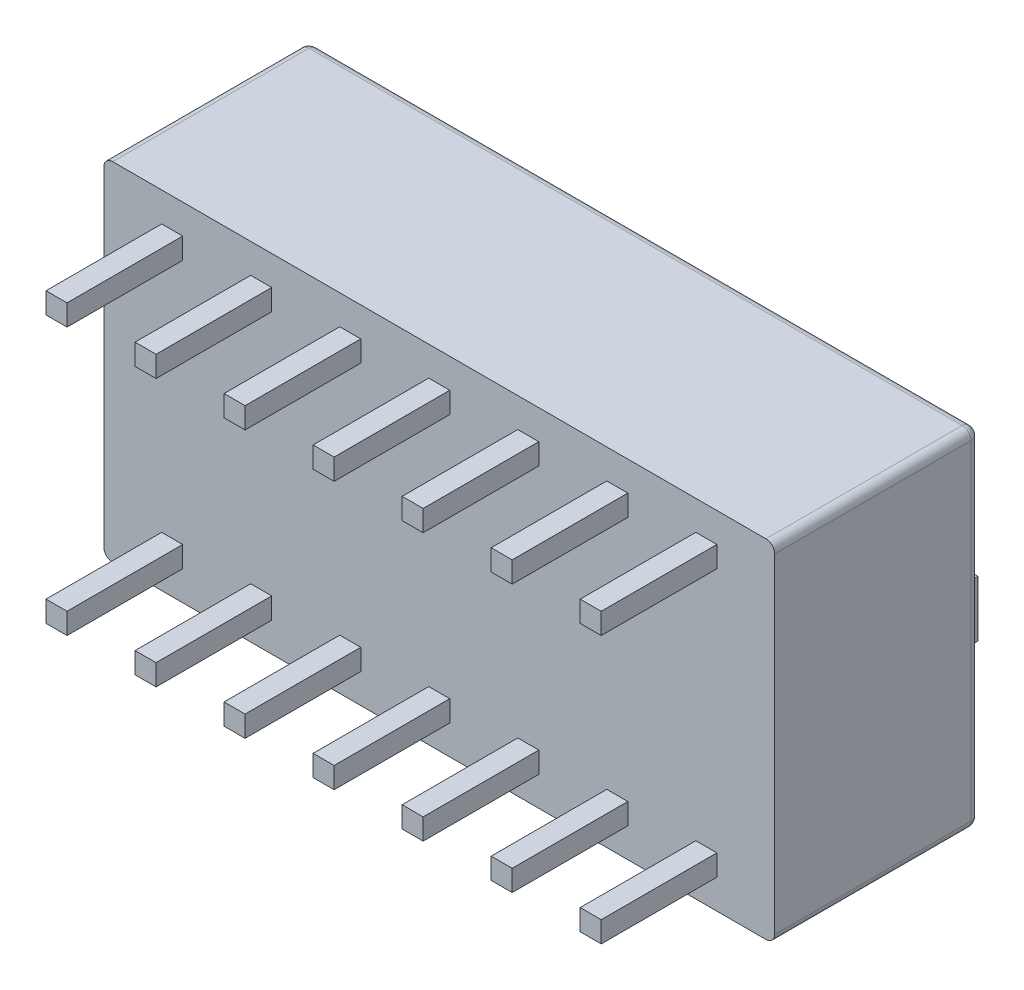
SolidWorks part; units mm, degrees
ref_plane "Ön Düzlem" through (0, 0, 0) normal (0, 0, 1) x (1, 0, 0)
ref_plane "Üst Düzlem" through (0, 0, 0) normal (0, 1, 0) x (1, 0, 0)
ref_plane "Sağ Düzlem" through (0, 0, 0) normal (1, 0, 0) x (0, 0, -1)
sketch "Çizim1" plane through (0, 0, 0) normal (0, 0, 1) x (1, 0, 0)
  line L1 (-9.57, 4.95) -> (9.57, 4.95)
  line L2 (-9.57, 4.95) -> (-9.57, -4.95)
  line L3 (-9.57, -4.95) -> (9.57, -4.95)
  line L4 (9.57, 4.95) -> (9.57, -4.95)
  line L5 (-9.57, 4.95) -> (9.57, -4.95) construction
  line L6 (-9.57, -4.95) -> (9.57, 4.95) construction
  point P0 (0, 0)
extrude "Yükseklik-Ekstrüzyon1" add sketch "Çizim1" along normal blind 5.85
sketch "Çizim2" plane through (0, 0, 0) normal (0, 0, -1) x (-1, 0, 0)
  line L8 (-8.32, 1.6) -> (-6.92, 1.6)
  line L9 (-8.32, 1.6) -> (-8.32, -1.6)
  line L10 (-8.32, -1.6) -> (-6.92, -1.6)
  line L11 (-6.92, 1.6) -> (-6.92, -1.6)
  line L12 (-8.32, 1.6) -> (-6.92, -1.6) construction
  line L13 (-8.32, -1.6) -> (-6.92, 1.6) construction
  line L14 (-5.78, 1.6) -> (-4.38, 1.6)
  line L15 (-5.78, 1.6) -> (-5.78, -1.6)
  line L16 (-5.78, -1.6) -> (-4.38, -1.6)
  line L17 (-4.38, 1.6) -> (-4.38, -1.6)
  line L18 (-5.78, 1.6) -> (-4.38, -1.6) construction
  line L19 (-5.78, -1.6) -> (-4.38, 1.6) construction
  line L20 (-3.24, 1.6) -> (-1.84, 1.6)
  line L21 (-3.24, 1.6) -> (-3.24, -1.6)
  line L22 (-3.24, -1.6) -> (-1.84, -1.6)
  line L23 (-1.84, 1.6) -> (-1.84, -1.6)
  line L24 (-3.24, 1.6) -> (-1.84, -1.6) construction
  line L25 (-3.24, -1.6) -> (-1.84, 1.6) construction
  line L26 (-0.7, 1.6) -> (0.7, 1.6)
  line L27 (-0.7, 1.6) -> (-0.7, -1.6)
  line L28 (-0.7, -1.6) -> (0.7, -1.6)
  line L29 (0.7, 1.6) -> (0.7, -1.6)
  line L30 (-0.7, 1.6) -> (0.7, -1.6) construction
  line L31 (-0.7, -1.6) -> (0.7, 1.6) construction
  line L32 (1.84, 1.6) -> (3.24, 1.6)
  line L33 (1.84, 1.6) -> (1.84, -1.6)
  line L34 (1.84, -1.6) -> (3.24, -1.6)
  line L35 (3.24, 1.6) -> (3.24, -1.6)
  line L36 (1.84, 1.6) -> (3.24, -1.6) construction
  line L37 (1.84, -1.6) -> (3.24, 1.6) construction
  line L38 (4.38, 1.6) -> (5.78, 1.6)
  line L39 (4.38, 1.6) -> (4.38, -1.6)
  line L40 (4.38, -1.6) -> (5.78, -1.6)
  line L41 (5.78, 1.6) -> (5.78, -1.6)
  line L42 (4.38, 1.6) -> (5.78, -1.6) construction
  line L43 (4.38, -1.6) -> (5.78, 1.6) construction
  line L44 (6.92, 1.6) -> (8.32, 1.6)
  line L45 (6.92, 1.6) -> (6.92, -1.6)
  line L46 (6.92, -1.6) -> (8.32, -1.6)
  line L47 (8.32, 1.6) -> (8.32, -1.6)
  line L48 (6.92, 1.6) -> (8.32, -1.6) construction
  line L49 (6.92, -1.6) -> (8.32, 1.6) construction
extrude "Kes-Ekstrüzyon1" cut sketch "Çizim2" against normal blind 1
sketch "Çizim3" plane through (0, 0, 1) normal (0, 0, -1) x (-1, 0, 0)
  line L0 (-6.92, -1.6) -> (-6.92, 1.6) construction
  line L1 (-8.32, -1.6) -> (-6.92, -1.6)
  line L2 (-8.32, -1.6) -> (-8.32, 0)
  line L3 (-8.32, 0) -> (-6.92, 0)
  line L4 (-6.92, -1.6) -> (-6.92, 0)
  line L5 (-5.78, 1.6) -> (-5.78, -1.6) construction
  line L6 (-5.78, 0) -> (-4.38, 0)
  line L7 (-5.78, 0) -> (-5.78, -1.6)
  line L8 (-5.78, -1.6) -> (-4.38, -1.6)
  line L9 (-4.38, 0) -> (-4.38, -1.6)
  line L10 (-3.24, 1.6) -> (-3.24, -1.6) construction
  line L11 (-3.24, 0) -> (-1.84, 0)
  line L12 (-3.24, 0) -> (-3.24, -1.6)
  line L13 (-3.24, -1.6) -> (-1.84, -1.6)
  line L14 (-1.84, 0) -> (-1.84, -1.6)
  line L15 (-0.7, 1.6) -> (-0.7, -1.6) construction
  line L16 (-0.7, 0) -> (0.7, 0)
  line L17 (-0.7, 0) -> (-0.7, -1.6)
  line L18 (-0.7, -1.6) -> (0.7, -1.6)
  line L19 (0.7, 0) -> (0.7, -1.6)
  line L20 (1.84, 1.6) -> (1.84, -1.6) construction
  line L21 (1.84, 0) -> (3.24, 0)
  line L22 (1.84, 0) -> (1.84, -1.6)
  line L23 (1.84, -1.6) -> (3.24, -1.6)
  line L24 (3.24, 0) -> (3.24, -1.6)
  line L25 (4.38, 1.6) -> (4.38, -1.6) construction
  line L26 (4.38, 0) -> (5.78, 0)
  line L27 (4.38, 0) -> (4.38, -1.6)
  line L28 (4.38, -1.6) -> (5.78, -1.6)
  line L29 (5.78, 0) -> (5.78, -1.6)
  line L30 (6.92, 1.6) -> (6.92, -1.6) construction
  line L31 (6.92, 0) -> (8.32, 0)
  line L32 (6.92, 0) -> (6.92, -1.6)
  line L33 (6.92, -1.6) -> (8.32, -1.6)
  line L34 (8.32, 0) -> (8.32, -1.6)
extrude "Yükseklik-Ekstrüzyon2" add sketch "Çizim3" along normal blind 2.2 separate body
sketch "Çizim4" plane through (0, 0, 1) normal (0, 0, -1) x (-1, 0, 0)
  line L0 (-6.92, -1.6) -> (-6.92, 1.6) construction
  line L1 (-8.32, 1.6) -> (-6.92, 1.6)
  line L2 (-8.32, 1.6) -> (-8.32, 0)
  line L3 (-8.32, 0) -> (-6.92, 0)
  line L4 (-6.92, 1.6) -> (-6.92, 0)
  line L5 (-4.38, -1.6) -> (-4.38, 1.6) construction
  line L6 (-5.78, 1.6) -> (-4.38, 1.6)
  line L7 (-5.78, 1.6) -> (-5.78, 0)
  line L8 (-5.78, 0) -> (-4.38, 0)
  line L9 (-4.38, 1.6) -> (-4.38, 0)
  line L10 (-1.84, -1.6) -> (-1.84, 1.6) construction
  line L11 (-3.24, 1.6) -> (-1.84, 1.6)
  line L12 (-3.24, 1.6) -> (-3.24, 0)
  line L13 (-3.24, 0) -> (-1.84, 0)
  line L14 (-1.84, 1.6) -> (-1.84, 0)
  line L15 (0.7, -1.6) -> (0.7, 1.6) construction
  line L16 (-0.7, 1.6) -> (0.7, 1.6)
  line L17 (-0.7, 1.6) -> (-0.7, 0)
  line L18 (-0.7, 0) -> (0.7, 0)
  line L19 (0.7, 1.6) -> (0.7, 0)
  line L20 (3.24, -1.6) -> (3.24, 1.6) construction
  line L21 (1.84, 1.6) -> (3.24, 1.6)
  line L22 (1.84, 1.6) -> (1.84, 0)
  line L23 (1.84, 0) -> (3.24, 0)
  line L24 (3.24, 1.6) -> (3.24, 0)
  line L25 (5.78, -1.6) -> (5.78, 1.6) construction
  line L26 (4.38, 1.6) -> (5.78, 1.6)
  line L27 (4.38, 1.6) -> (4.38, 0)
  line L28 (4.38, 0) -> (5.78, 0)
  line L29 (5.78, 1.6) -> (5.78, 0)
  line L31 (6.92, 1.6) -> (8.32, 1.6)
  line L32 (6.92, 1.6) -> (6.92, 0)
  line L33 (6.92, 0) -> (8.32, 0)
  line L34 (8.32, 1.6) -> (8.32, 0)
extrude "Yükseklik-Ekstrüzyon3" add sketch "Çizim4" along normal blind 0.9 separate body
fillet "Radyus1" radius 0.25 8 edges at (9.57, -4.95, 2.925) (9.57, 4.95, 2.925) (9.57, 0, 0) (-9.57, -4.95, 2.925) (0, -4.95, 0) (0, 4.95, 0) (-9.57, 4.95, 2.925) (-9.57, 0, 0)
sketch "Çizim5" plane through (0, 0, 5.85) normal (0, 0, 1) x (1, 0, 0)
  line L15 (-7.92, 4.11) -> (-7.32, 4.11)
  line L16 (-7.92, 4.11) -> (-7.92, 3.51)
  line L17 (-7.92, 3.51) -> (-7.32, 3.51)
  line L18 (-7.32, 4.11) -> (-7.32, 3.51)
  line L19 (-7.92, 4.11) -> (-7.32, 3.51) construction
  line L20 (-7.92, 3.51) -> (-7.32, 4.11) construction
  line L21 (-5.38, 4.11) -> (-4.78, 4.11)
  line L22 (-5.38, 4.11) -> (-5.38, 3.51)
  line L23 (-5.38, 3.51) -> (-4.78, 3.51)
  line L24 (-4.78, 4.11) -> (-4.78, 3.51)
  line L25 (-5.38, 4.11) -> (-4.78, 3.51) construction
  line L26 (-5.38, 3.51) -> (-4.78, 4.11) construction
  line L27 (-2.84, 4.11) -> (-2.24, 4.11)
  line L28 (-2.84, 4.11) -> (-2.84, 3.51)
  line L29 (-2.84, 3.51) -> (-2.24, 3.51)
  line L30 (-2.24, 4.11) -> (-2.24, 3.51)
  line L31 (-2.84, 4.11) -> (-2.24, 3.51) construction
  line L32 (-2.84, 3.51) -> (-2.24, 4.11) construction
  line L33 (-0.3, 4.11) -> (0.3, 4.11)
  line L34 (-0.3, 4.11) -> (-0.3, 3.51)
  line L35 (-0.3, 3.51) -> (0.3, 3.51)
  line L36 (0.3, 4.11) -> (0.3, 3.51)
  line L37 (-0.3, 4.11) -> (0.3, 3.51) construction
  line L38 (-0.3, 3.51) -> (0.3, 4.11) construction
  line L39 (2.24, 4.11) -> (2.84, 4.11)
  line L40 (2.24, 4.11) -> (2.24, 3.51)
  line L41 (2.24, 3.51) -> (2.84, 3.51)
  line L42 (2.84, 4.11) -> (2.84, 3.51)
  line L43 (2.24, 4.11) -> (2.84, 3.51) construction
  line L44 (2.24, 3.51) -> (2.84, 4.11) construction
  line L45 (4.78, 4.11) -> (5.38, 4.11)
  line L46 (4.78, 4.11) -> (4.78, 3.51)
  line L47 (4.78, 3.51) -> (5.38, 3.51)
  line L48 (5.38, 4.11) -> (5.38, 3.51)
  line L49 (4.78, 4.11) -> (5.38, 3.51) construction
  line L50 (4.78, 3.51) -> (5.38, 4.11) construction
  line L51 (7.32, 4.11) -> (7.92, 4.11)
  line L52 (7.32, 4.11) -> (7.32, 3.51)
  line L53 (7.32, 3.51) -> (7.92, 3.51)
  line L54 (7.92, 4.11) -> (7.92, 3.51)
  line L55 (7.32, 4.11) -> (7.92, 3.51) construction
  line L56 (7.32, 3.51) -> (7.92, 4.11) construction
  line L57 (7.92, -4.11) -> (7.32, -4.11)
  line L58 (7.92, -4.11) -> (7.92, -3.51)
  line L59 (7.92, -3.51) -> (7.32, -3.51)
  line L60 (7.32, -4.11) -> (7.32, -3.51)
  line L61 (7.92, -4.11) -> (7.32, -3.51) construction
  line L62 (7.92, -3.51) -> (7.32, -4.11) construction
  line L63 (5.38, -4.11) -> (4.78, -4.11)
  line L64 (5.38, -4.11) -> (5.38, -3.51)
  line L65 (5.38, -3.51) -> (4.78, -3.51)
  line L66 (4.78, -4.11) -> (4.78, -3.51)
  line L67 (5.38, -4.11) -> (4.78, -3.51) construction
  line L68 (5.38, -3.51) -> (4.78, -4.11) construction
  line L69 (2.24, -3.51) -> (2.84, -3.51)
  line L70 (2.24, -3.51) -> (2.24, -4.11)
  line L71 (2.24, -4.11) -> (2.84, -4.11)
  line L72 (2.84, -3.51) -> (2.84, -4.11)
  line L73 (2.24, -3.51) -> (2.84, -4.11) construction
  line L74 (2.24, -4.11) -> (2.84, -3.51) construction
  line L75 (-0.3, -3.51) -> (0.3, -3.51)
  line L76 (-0.3, -3.51) -> (-0.3, -4.11)
  line L77 (-0.3, -4.11) -> (0.3, -4.11)
  line L78 (0.3, -3.51) -> (0.3, -4.11)
  line L79 (-0.3, -3.51) -> (0.3, -4.11) construction
  line L80 (-0.3, -4.11) -> (0.3, -3.51) construction
  line L81 (-2.84, -3.51) -> (-2.24, -3.51)
  line L82 (-2.84, -3.51) -> (-2.84, -4.11)
  line L83 (-2.84, -4.11) -> (-2.24, -4.11)
  line L84 (-2.24, -3.51) -> (-2.24, -4.11)
  line L85 (-2.84, -3.51) -> (-2.24, -4.11) construction
  line L86 (-2.84, -4.11) -> (-2.24, -3.51) construction
  line L87 (-5.38, -3.51) -> (-4.78, -3.51)
  line L88 (-5.38, -3.51) -> (-5.38, -4.11)
  line L89 (-5.38, -4.11) -> (-4.78, -4.11)
  line L90 (-4.78, -3.51) -> (-4.78, -4.11)
  line L91 (-5.38, -3.51) -> (-4.78, -4.11) construction
  line L92 (-5.38, -4.11) -> (-4.78, -3.51) construction
  line L93 (-7.92, -4.11) -> (-7.32, -4.11)
  line L94 (-7.92, -4.11) -> (-7.92, -3.51)
  line L95 (-7.92, -3.51) -> (-7.32, -3.51)
  line L96 (-7.32, -4.11) -> (-7.32, -3.51)
  line L97 (-7.92, -4.11) -> (-7.32, -3.51) construction
  line L98 (-7.92, -3.51) -> (-7.32, -4.11) construction
extrude "Yükseklik-Ekstrüzyon4" add sketch "Çizim5" along normal blind 3.3
